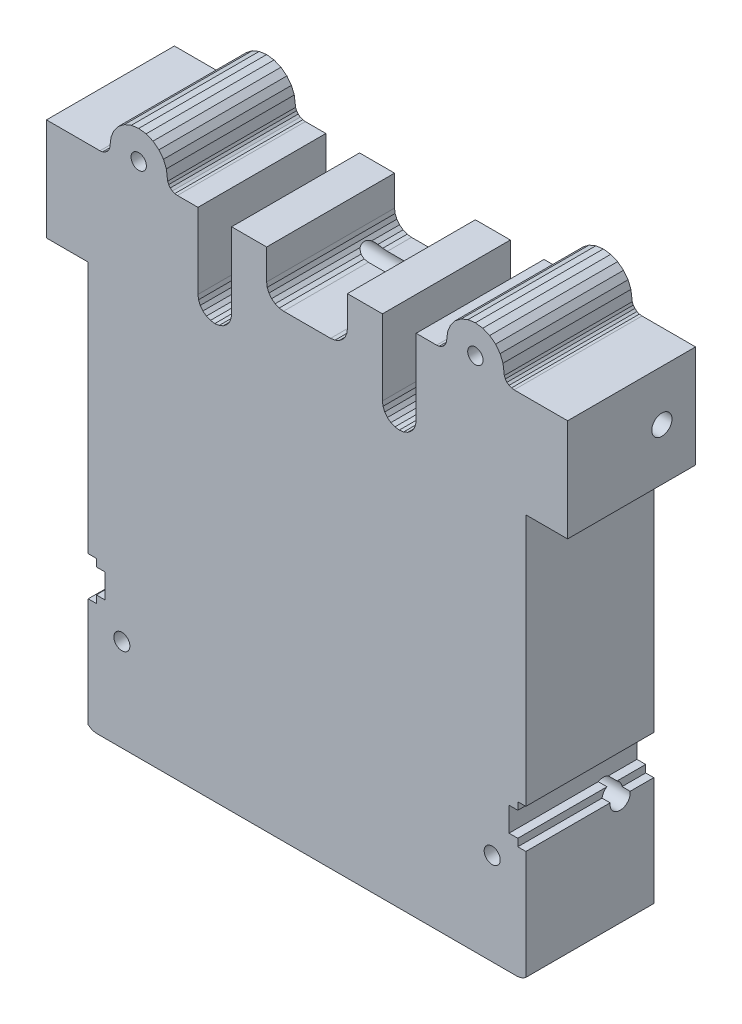
SolidWorks part; units mm, degrees
ref_plane "Alzado" through (0, 0, 0) normal (0, 0, 1) x (1, 0, 0)
ref_plane "Planta" through (0, 0, 0) normal (0, 1, 0) x (1, 0, 0)
ref_plane "Vista lateral" through (0, 0, 0) normal (1, 0, 0) x (0, 0, -1)
sketch "Croquis3" plane through (0, 0, 0) normal (0, 0, 1) x (1, 0, 0)
  line L0 (62, 600) -> (62, 225)
  line L1 (62, 225) -> (74, 225)
  line L2 (74, 225) -> (74, 214)
  line L3 (74, 214) -> (87, 214)
  line L4 (87, 214) -> (87, 178)
  line L5 (87, 178) -> (74, 178)
  line L6 (74, 178) -> (74, 167)
  line L7 (52, 590) -> (52, 215)
  line L8 (74, 167) -> (62, 167)
  line L9 (62, 167) -> (62, 5)
  line L10 (62, 5) -> (65.9604, 2.275)
  line L11 (65.9604, 2.275) -> (70.4573, 0.5755)
  line L12 (70.4573, 0.5755) -> (75.23, 0)
  line L13 (75.23, 0) -> (698.7963, 0)
  line L14 (698.7963, 0) -> (703.5598, 0.5797)
  line L15 (703.5598, 0.5797) -> (708.0474, 2.2791)
  line L16 (708.0474, 2.2791) -> (712, 5)
  line L17 (712, 5) -> (712, 167)
  line L18 (712, 167) -> (700, 167)
  line L19 (700, 167) -> (700, 178)
  line L20 (700, 178) -> (687, 178)
  line L21 (687, 178) -> (687, 214)
  line L22 (687, 214) -> (700, 214)
  line L23 (700, 214) -> (700, 225)
  line L24 (700, 225) -> (712, 225)
  line L25 (712, 225) -> (712, 600)
  line L26 (712, 600) -> (774, 600)
  line L27 (774, 600) -> (774, 752)
  line L28 (774, 752) -> (694.5094, 752)
  line L29 (694.5094, 752) -> (690.6256, 752.51)
  line L30 (690.6256, 752.51) -> (687.0052, 754.0081)
  line L31 (687.0052, 754.0081) -> (683.897, 756.3907)
  line L32 (683.897, 756.3907) -> (681.5118, 759.497)
  line L33 (681.5118, 759.497) -> (680.0116, 763.1165)
  line L34 (680.0116, 763.1165) -> (679.4991, 767.0001)
  line L35 (679.4991, 767.0001) -> (678.0477, 777.9984)
  line L36 (678.0477, 777.9984) -> (673.8005, 788.2468)
  line L37 (673.8005, 788.2468) -> (667.0465, 797.0475)
  line L38 (667.0465, 797.0475) -> (658.2458, 803.8014)
  line L39 (658.2458, 803.8014) -> (647.9974, 808.0487)
  line L40 (647.9974, 808.0487) -> (636.9991, 809.5001)
  line L41 (636.9991, 809.5001) -> (626.0008, 808.0487)
  line L42 (626.0008, 808.0487) -> (615.7524, 803.8014)
  line L43 (615.7524, 803.8014) -> (606.9516, 797.0475)
  line L44 (606.9516, 797.0475) -> (600.1977, 788.2468)
  line L45 (600.1977, 788.2468) -> (595.9505, 777.9984)
  line L46 (595.9505, 777.9984) -> (594.499, 767.0001)
  line L47 (594.499, 767.0001) -> (593.9868, 763.1183)
  line L48 (593.9868, 763.1183) -> (592.4877, 759.5012)
  line L49 (592.4877, 759.5012) -> (590.1039, 756.3951)
  line L50 (590.1039, 756.3951) -> (586.9977, 754.0113)
  line L51 (586.9977, 754.0113) -> (583.3807, 752.5123)
  line L52 (583.3807, 752.5123) -> (579.4989, 752)
  line L53 (579.4989, 752) -> (548.9991, 752)
  line L54 (548.9991, 752) -> (548.9991, 639.9991)
  line L55 (548.9991, 639.9991) -> (548.1472, 633.5286)
  line L56 (548.1472, 633.5286) -> (545.6497, 627.4991)
  line L57 (545.6497, 627.4991) -> (541.6767, 622.3214)
  line L58 (541.6767, 622.3214) -> (536.499, 618.3484)
  line L59 (536.499, 618.3484) -> (530.4695, 615.8509)
  line L60 (530.4695, 615.8509) -> (523.9991, 614.9991)
  line L61 (523.9991, 614.9991) -> (517.5286, 615.8509)
  line L62 (517.5286, 615.8509) -> (511.4991, 618.3484)
  line L63 (511.4991, 618.3484) -> (506.3213, 622.3214)
  line L64 (506.3213, 622.3214) -> (502.3484, 627.4991)
  line L65 (502.3484, 627.4991) -> (499.8509, 633.5286)
  line L66 (499.8509, 633.5286) -> (498.9991, 639.9991)
  line L67 (498.9991, 639.9991) -> (498.9991, 752)
  line L68 (498.9991, 752) -> (446.9989, 752)
  line L69 (446.9989, 752) -> (446.9989, 707.1898)
  line L70 (446.9989, 707.1898) -> (446.1684, 700.6915)
  line L71 (446.1684, 700.6915) -> (443.6843, 694.6296)
  line L72 (443.6843, 694.6296) -> (439.7159, 689.4172)
  line L73 (439.7159, 689.4172) -> (434.5337, 685.4095)
  line L74 (434.5337, 685.4095) -> (428.4907, 682.8796)
  line L75 (428.4907, 682.8796) -> (421.9989, 682)
  line L76 (421.9989, 682) -> (352.1887, 682)
  line L77 (352.1887, 682) -> (345.6904, 682.8305)
  line L78 (345.6904, 682.8305) -> (339.6285, 685.3146)
  line L79 (339.6285, 685.3146) -> (334.4161, 689.283)
  line L80 (334.4161, 689.283) -> (330.4084, 694.4652)
  line L81 (330.4084, 694.4652) -> (327.8786, 700.5082)
  line L82 (327.8786, 700.5082) -> (326.9989, 707)
  line L83 (326.9989, 707) -> (326.9989, 752)
  line L84 (326.9989, 752) -> (274.999, 752)
  line L85 (274.999, 752) -> (274.999, 639.9991)
  line L86 (274.999, 639.9991) -> (274.1472, 633.5286)
  line L87 (274.1472, 633.5286) -> (271.6497, 627.4991)
  line L88 (271.6497, 627.4991) -> (267.6767, 622.3214)
  line L89 (267.6767, 622.3214) -> (262.499, 618.3484)
  line L90 (262.499, 618.3484) -> (256.4695, 615.8509)
  line L91 (256.4695, 615.8509) -> (249.999, 614.9991)
  line L92 (249.999, 614.9991) -> (243.5285, 615.8509)
  line L93 (243.5285, 615.8509) -> (237.499, 618.3484)
  line L94 (237.499, 618.3484) -> (232.3214, 622.3214)
  line L95 (232.3214, 622.3214) -> (228.3484, 627.4991)
  line L96 (228.3484, 627.4991) -> (225.8509, 633.5286)
  line L97 (225.8509, 633.5286) -> (224.999, 639.9991)
  line L98 (224.999, 639.9991) -> (224.999, 752)
  line L99 (224.999, 752) -> (194.5099, 752)
  line L100 (194.5099, 752) -> (190.626, 752.51)
  line L101 (190.626, 752.51) -> (187.0075, 754.0081)
  line L102 (187.0075, 754.0081) -> (183.8992, 756.3907)
  line L103 (183.8992, 756.3907) -> (181.5141, 759.497)
  line L104 (181.5141, 759.497) -> (180.0126, 763.1165)
  line L105 (180.0126, 763.1165) -> (179.5001, 767.0001)
  line L106 (179.5001, 767.0001) -> (178.0486, 777.9984)
  line L107 (178.0486, 777.9984) -> (173.8014, 788.2468)
  line L108 (173.8014, 788.2468) -> (167.0475, 797.0475)
  line L109 (167.0475, 797.0475) -> (158.2467, 803.8014)
  line L110 (158.2467, 803.8014) -> (147.9983, 808.0487)
  line L111 (147.9983, 808.0487) -> (137, 809.5001)
  line L112 (137, 809.5001) -> (126.0017, 808.0487)
  line L113 (126.0017, 808.0487) -> (115.7533, 803.8014)
  line L114 (115.7533, 803.8014) -> (106.9525, 797.0475)
  line L115 (106.9525, 797.0475) -> (100.1986, 788.2468)
  line L116 (100.1986, 788.2468) -> (95.9514, 777.9984)
  line L117 (95.9514, 777.9984) -> (94.4999, 767.0001)
  line L118 (94.4999, 767.0001) -> (93.9877, 763.1183)
  line L119 (93.9877, 763.1183) -> (92.4886, 759.5012)
  line L120 (92.4886, 759.5012) -> (90.1049, 756.3951)
  line L121 (90.1049, 756.3951) -> (86.9987, 754.0113)
  line L122 (86.9987, 754.0113) -> (83.3816, 752.5123)
  line L123 (83.3816, 752.5123) -> (79.4999, 752)
  line L124 (79.4999, 752) -> (0, 752)
  line L125 (0, 752) -> (0, 600)
  line L126 (0, 600) -> (62, 600)
  line L127 (124, 137) -> (100, 137) construction
  line L128 (674, 137) -> (650, 137) construction
  line L129 (52, 215) -> (64, 215)
  line L130 (64, 215) -> (64, 204)
  line L131 (64, 204) -> (77, 204)
  line L132 (77, 204) -> (77, 188)
  line L133 (77, 188) -> (64, 188)
  line L134 (64, 188) -> (64, 177)
  line L135 (64, 177) -> (52, 177)
  line L136 (52, 177) -> (52, -0.2579)
  line L137 (52, -0.2579) -> (61.2909, -6.6506)
  line L138 (61.2909, -6.6506) -> (68.0563, -9.2074)
  line L139 (68.0563, -9.2074) -> (74.6293, -10)
  line L140 (74.6293, -10) -> (699.4026, -10)
  line L141 (699.4026, -10) -> (705.9693, -9.2008)
  line L142 (705.9693, -9.2008) -> (712.7207, -6.6442)
  line L143 (712.7207, -6.6442) -> (722, -0.2565)
  line L144 (722, -0.2565) -> (722, 177)
  line L145 (722, 177) -> (710, 177)
  line L146 (710, 177) -> (710, 188)
  line L147 (710, 188) -> (697, 188)
  line L148 (697, 188) -> (697, 204)
  line L149 (697, 204) -> (710, 204)
  line L150 (710, 204) -> (710, 215)
  line L151 (710, 215) -> (722, 215)
  line L152 (722, 215) -> (722, 590)
  line L153 (722, 590) -> (784, 590)
  line L154 (784, 590) -> (784, 762)
  line L155 (784, 762) -> (695.1631, 762)
  line L156 (695.1631, 762) -> (693.2327, 762.2535)
  line L157 (693.2327, 762.2535) -> (692.0446, 762.7451)
  line L158 (692.0446, 762.7451) -> (691.0262, 763.5258)
  line L159 (691.0262, 763.5258) -> (690.2455, 764.5426)
  line L160 (690.2455, 764.5426) -> (689.7535, 765.7297)
  line L161 (689.7535, 765.7297) -> (689.4131, 768.3084)
  line L162 (689.4131, 768.3084) -> (687.7896, 780.6113)
  line L163 (687.7896, 780.6113) -> (682.5347, 793.291)
  line L164 (682.5347, 793.291) -> (674.1786, 804.1795)
  line L165 (674.1786, 804.1795) -> (663.29, 812.5357)
  line L166 (663.29, 812.5357) -> (650.6103, 817.7905)
  line L167 (650.6103, 817.7905) -> (636.9991, 819.5868)
  line L168 (636.9991, 819.5868) -> (623.3879, 817.7905)
  line L169 (623.3879, 817.7905) -> (610.7082, 812.5357)
  line L170 (610.7082, 812.5357) -> (599.8196, 804.1795)
  line L171 (599.8196, 804.1795) -> (591.4634, 793.291)
  line L172 (591.4634, 793.291) -> (586.2086, 780.6113)
  line L173 (586.2086, 780.6113) -> (584.585, 768.3084)
  line L174 (584.585, 768.3084) -> (584.2449, 765.7312)
  line L175 (584.2449, 765.7312) -> (583.7535, 764.5455)
  line L176 (583.7535, 764.5455) -> (582.972, 763.5272)
  line L177 (582.972, 763.5272) -> (581.9536, 762.7456)
  line L178 (581.9536, 762.7456) -> (580.7678, 762.2542)
  line L179 (580.7678, 762.2542) -> (578.8419, 762)
  line L180 (578.8419, 762) -> (538.9991, 762)
  line L181 (538.9991, 762) -> (538.9991, 640.6545)
  line L182 (538.9991, 640.6545) -> (538.4046, 636.1391)
  line L183 (538.4046, 636.1391) -> (536.9147, 632.5422)
  line L184 (536.9147, 632.5422) -> (534.5446, 629.4535)
  line L185 (534.5446, 629.4535) -> (531.4559, 627.0834)
  line L186 (531.4559, 627.0834) -> (527.859, 625.5935)
  line L187 (527.859, 625.5935) -> (523.9991, 625.0853)
  line L188 (523.9991, 625.0853) -> (520.1391, 625.5935)
  line L189 (520.1391, 625.5935) -> (516.5422, 627.0834)
  line L190 (516.5422, 627.0834) -> (513.4534, 629.4535)
  line L191 (513.4534, 629.4535) -> (511.0834, 632.5422)
  line L192 (511.0834, 632.5422) -> (509.5935, 636.1391)
  line L193 (509.5935, 636.1391) -> (508.9991, 640.6545)
  line L194 (508.9991, 640.6545) -> (508.9991, 762)
  line L195 (508.9991, 762) -> (436.9989, 762)
  line L196 (436.9989, 762) -> (436.9989, 707.8262)
  line L197 (436.9989, 707.8262) -> (436.416, 703.2652)
  line L198 (436.416, 703.2652) -> (434.9303, 699.6397)
  line L199 (434.9303, 699.6397) -> (432.5569, 696.5223)
  line L200 (432.5569, 696.5223) -> (429.4575, 694.1254)
  line L201 (429.4575, 694.1254) -> (425.8434, 692.6123)
  line L202 (425.8434, 692.6123) -> (421.3245, 692)
  line L203 (421.3245, 692) -> (352.8251, 692)
  line L204 (352.8251, 692) -> (348.2641, 692.5829)
  line L205 (348.2641, 692.5829) -> (344.6386, 694.0686)
  line L206 (344.6386, 694.0686) -> (341.5212, 696.442)
  line L207 (341.5212, 696.442) -> (339.1243, 699.5414)
  line L208 (339.1243, 699.5414) -> (337.6112, 703.1555)
  line L209 (337.6112, 703.1555) -> (336.9989, 707.6745)
  line L210 (336.9989, 707.6745) -> (336.9989, 762)
  line L211 (336.9989, 762) -> (264.999, 762)
  line L212 (264.999, 762) -> (264.999, 640.6545)
  line L213 (264.999, 640.6545) -> (264.4046, 636.1391)
  line L214 (264.4046, 636.1391) -> (262.9147, 632.5422)
  line L215 (262.9147, 632.5422) -> (260.5446, 629.4535)
  line L216 (260.5446, 629.4535) -> (257.4559, 627.0834)
  line L217 (257.4559, 627.0834) -> (253.859, 625.5935)
  line L218 (253.859, 625.5935) -> (249.999, 625.0853)
  line L219 (249.999, 625.0853) -> (246.1391, 625.5935)
  line L220 (246.1391, 625.5935) -> (242.5422, 627.0834)
  line L221 (242.5422, 627.0834) -> (239.4534, 629.4535)
  line L222 (239.4534, 629.4535) -> (237.0834, 632.5422)
  line L223 (237.0834, 632.5422) -> (235.5935, 636.1391)
  line L224 (235.5935, 636.1391) -> (234.999, 640.6545)
  line L225 (234.999, 640.6545) -> (234.999, 762)
  line L226 (234.999, 762) -> (195.1636, 762)
  line L227 (195.1636, 762) -> (193.2341, 762.2534)
  line L228 (193.2341, 762.2534) -> (192.0476, 762.7446)
  line L229 (192.0476, 762.7446) -> (191.0285, 763.5258)
  line L230 (191.0285, 763.5258) -> (190.2468, 764.5439)
  line L231 (190.2468, 764.5439) -> (189.7542, 765.7313)
  line L232 (189.7542, 765.7313) -> (189.4141, 768.3084)
  line L233 (189.4141, 768.3084) -> (187.7905, 780.6113)
  line L234 (187.7905, 780.6113) -> (182.5357, 793.291)
  line L235 (182.5357, 793.291) -> (174.1795, 804.1795)
  line L236 (174.1795, 804.1795) -> (163.2909, 812.5357)
  line L237 (163.2909, 812.5357) -> (150.6112, 817.7905)
  line L238 (150.6112, 817.7905) -> (137, 819.5868)
  line L239 (137, 819.5868) -> (123.3888, 817.7905)
  line L240 (123.3888, 817.7905) -> (110.7091, 812.5357)
  line L241 (110.7091, 812.5357) -> (99.8205, 804.1795)
  line L242 (99.8205, 804.1795) -> (91.4643, 793.291)
  line L243 (91.4643, 793.291) -> (86.2095, 780.6113)
  line L244 (86.2095, 780.6113) -> (84.5859, 768.3084)
  line L245 (84.5859, 768.3084) -> (84.2458, 765.7312)
  line L246 (84.2458, 765.7312) -> (83.7543, 764.5454)
  line L247 (83.7543, 764.5454) -> (82.9729, 763.5271)
  line L248 (82.9729, 763.5271) -> (81.9545, 762.7456)
  line L249 (81.9545, 762.7456) -> (80.7687, 762.2542)
  line L250 (80.7687, 762.2542) -> (78.8429, 762)
  line L251 (78.8429, 762) -> (-10, 762)
  line L252 (-10, 762) -> (-10, 590)
  line L253 (-10, 590) -> (52, 590)
  line L254 (124, 147) -> (100, 147)
  line L255 (674, 147) -> (650, 147)
  circle A0 centre (137, 767.0001) radius 11.4017
  circle A1 centre (636.9991, 767.0001) radius 11.4017
  circle A2 centre (112, 137) radius 11.8973
  circle A3 centre (662, 137) radius 11.8974
  circle A4 centre (137, 767.0001) radius 21.4017
  circle A5 centre (636.9991, 767.0001) radius 21.4017
  circle A6 centre (112, 137) radius 21.8973
  circle A7 centre (662, 137) radius 21.8974
  point P16 (387.0132, 0)
  dimension "D4" = 23.7947
  dimension "D5" = 22.8033
  dimension "D6" = 23.7947
  dimension "D7" = 22.8033
  dimension "D1" = 623.5663
  dimension "D2" = 62
  dimension "D3" = 375
  dimension "D8" = 65.9604
  dimension "D9" = 70.4573
  dimension "D10" = 74
  dimension "D12" = 75.23
  dimension "D13" = 79.4999
  dimension "D14" = 83.3816
  dimension "D15" = 87
  dimension "D16" = 86.9987
  dimension "D17" = 90.1049
  dimension "D18" = 92.4886
  dimension "D19" = 93.9877
  dimension "D20" = 95.9514
  dimension "D21" = 100.1986
  dimension "D22" = 106.9525
  dimension "D23" = 112
  dimension "D24" = 115.7533
  dimension "D25" = 180.0126
  dimension "D26" = 181.5141
  dimension "D27" = 183.8992
  dimension "D28" = 187.0075
  dimension "D29" = 190.626
  dimension "D30" = 194.5099
  dimension "D31" = 224.999
  dimension "D32" = 225.8509
  dimension "D33" = 228.3484
  dimension "D34" = 232.3214
  dimension "D35" = 237.499
  dimension "D36" = 243.5285
  dimension "D37" = 249.999
  dimension "D38" = 256.4695
  dimension "D39" = 498.9991
  dimension "D40" = 579.4989
  dimension "D41" = 636.9991
  dimension "D42" = 658.2458
  dimension "D43" = 681.5118
  dimension "D44" = 690.6256
  dimension "D45" = 0.5755
  dimension "D46" = 0.5797
  dimension "D47" = 2.275
  dimension "D48" = 2.2791
  dimension "D49" = 137
  dimension "D50" = 167
  dimension "D51" = 178
  dimension "D52" = 326.9989
  dimension "D53" = 327.8786
  dimension "D54" = 330.4084
  dimension "D55" = 334.4161
  dimension "D56" = 339.6285
  dimension "D57" = 345.6904
  dimension "D58" = 352.1887
  dimension "D59" = 214
  dimension "D60" = 421.9989
  dimension "D61" = 428.4907
  dimension "D62" = 434.5337
  dimension "D63" = 439.7159
  dimension "D64" = 443.6843
  dimension "D65" = 446.1684
  dimension "D66" = 446.9989
  dimension "D67" = 614.9991
  dimension "D68" = 682
  dimension "D69" = 682.8305
  dimension "D70" = 682.8796
  dimension "D71" = 694.6296
  dimension "D72" = 700.6915
  dimension "D73" = 707
  dimension "D74" = 752
  dimension "D75" = 10
  dimension "D95" = 662
  dimension "D103" = 687
  dimension "D107" = 700
  dimension "D108" = 703.5598
  dimension "D109" = 708.0474
  dimension "D110" = 712
  dimension "D111" = 774
extrude "Saliente-Extruir3" add sketch "Croquis3" along normal blind 190 contours L0 L1 L2 L3 L4 L5 L6 L8 L9 L10 L11 L12 L13 L14 L15 L16 L17 L18 L19 L20 L21 L22 L23 L24 L25 L26 L27 L28 L29 L30 L31 L32 L33 L34 L35 L36 L37 L38 L39 L40 L41 L42 L43 L44 L45 L46 L47 L48 L49 L50 L51 L52 L53 L54 L55 L56 L57 L58 L59 L60 L61 L62 L63 L64 L65 L66 L67 L68 L69 L70 L71 L72 L73 L74 L75 L76 L77 L78 L79 L80 L81 L82 L83 L84 L85 L86 L87 L88 L89 L90 L91 L92 L93 L94 L95 L96 L97 L98 L99 L100 L101 L102 L103 L104 L105 L106 L107 L108 L109 L110 L111 L112 L113 L114 L115 L116 L117 L118 L119 L120 L121 L122 L123 L124 L125 L126 | A0 | A1 | A3 | A2
scale "Escala1" bodies to scale 103 scale about centroid uniform scaling yes scale factor 0.1
sketch "Croquis4" plane through (348.3001, 0, 0) normal (-1, 0, 0) x (0, 0, 1)
  line L0 (85.5, 418.1462) -> (85.5, 402.9462) construction
  line L1 (85.5, 359.6462) -> (85.5, 343.4462) construction
  line L2 (104.5, 418.1462) -> (85.5, 418.1462) construction
  line L3 (104.5, 343.4462) -> (85.5, 343.4462) construction
  circle A0 centre (90.5, 410.6462) radius 1.5
  circle A1 centre (90.5, 359.4462) radius 1.5
  dimension "D1" = 3
  dimension "D2" = 5
  dimension "D3" = 3
  dimension "D4" = 5
  dimension "D5" = 16
  dimension "D6" = 7.5
extrude "Cortar-Extruir1" cut sketch "Croquis4" against normal up to surface (77.4 mm away) up to face at (425.7001, 410.5462, 95)
